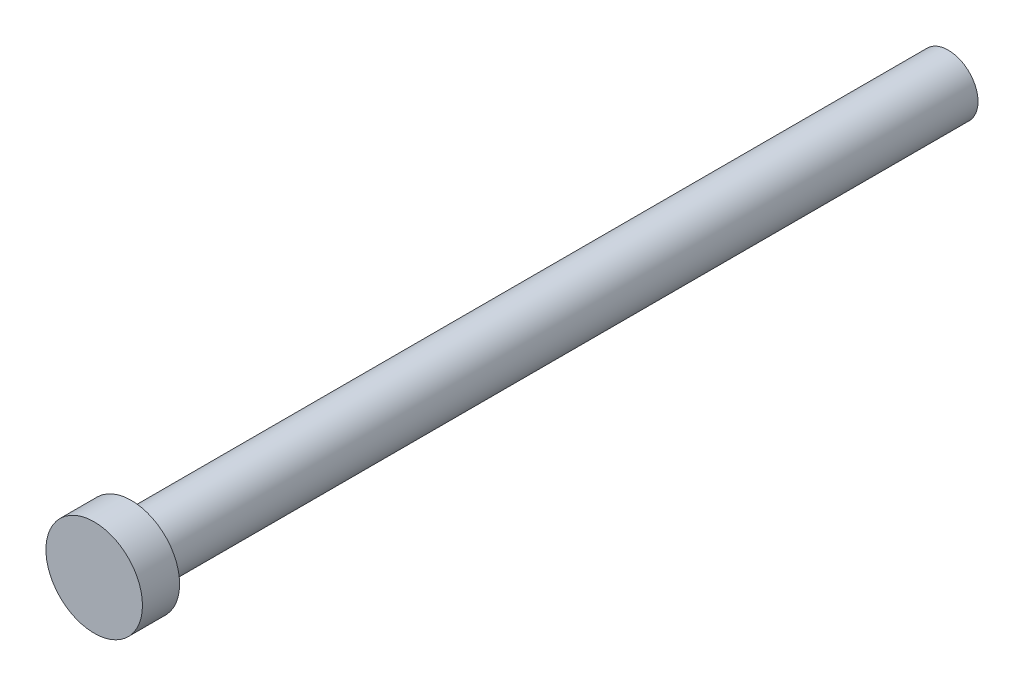
SolidWorks part; units mm, degrees
ref_plane "Front Plane" through (0, 0, 0) normal (0, 0, 1) x (1, 0, 0)
ref_plane "Top Plane" through (0, 0, 0) normal (0, 1, 0) x (1, 0, 0)
ref_plane "Right Plane" through (0, 0, 0) normal (1, 0, 0) x (0, 0, -1)
sketch "Sketch1" plane through (0, 0, 0) normal (0, 0, 1) x (1, 0, 0)
  circle A0 centre (0, 0) radius 4
  dimension "D1" = 8
extrude "Boss-Extrude1" add sketch "Sketch1" along normal blind 110
sketch "Sketch2" plane through (0, 0, 110) normal (0, 0, 1) x (1, 0, 0)
  circle A0 centre (0, 0) radius 6.5
  dimension "D1" = 13
extrude "Boss-Extrude2" add sketch "Sketch2" along normal blind 5
